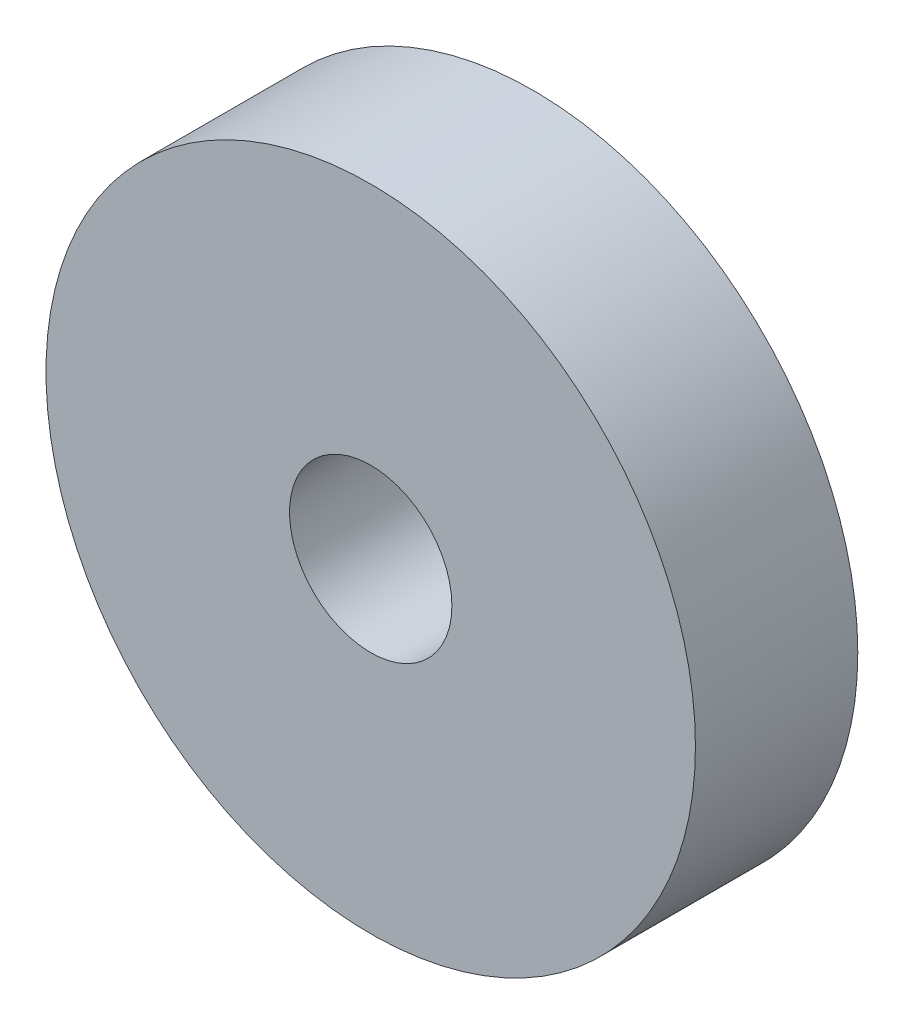
SolidWorks part; units mm, degrees
ref_plane "Front Plane" through (0, 0, 0) normal (0, 0, 1) x (1, 0, 0)
ref_plane "Top Plane" through (0, 0, 0) normal (0, 1, 0) x (1, 0, 0)
ref_plane "Right Plane" through (0, 0, 0) normal (1, 0, 0) x (0, 0, -1)
sketch "Sketch1" plane through (0, 0, 0) normal (0, 0, 1) x (1, 0, 0)
  circle A0 centre (0, 0) radius 50.8
  circle A1 centre (0, 0) radius 25.4
  circle A2 centre (0, 0) radius 6.35
  dimension "D1" = 50.8
  dimension "D2" = 101.6
  dimension "D3" = 12.7
extrude "Boss-Extrude1" [suppressed] add sketch "Sketch1" along normal blind 12.7 contours A1 A2 | A0 A1
sketch "Sketch2" plane through (0, 0, 0) normal (0, 0, 1) x (1, 0, 0)
  circle A0 centre (0, 0) radius 6.35
  circle A1 centre (0, 0) radius 25.4
  dimension "D1" = 12.7
  dimension "D2" = 50.8
extrude "Boss-Extrude2" add sketch "Sketch2" along normal blind 12.7
